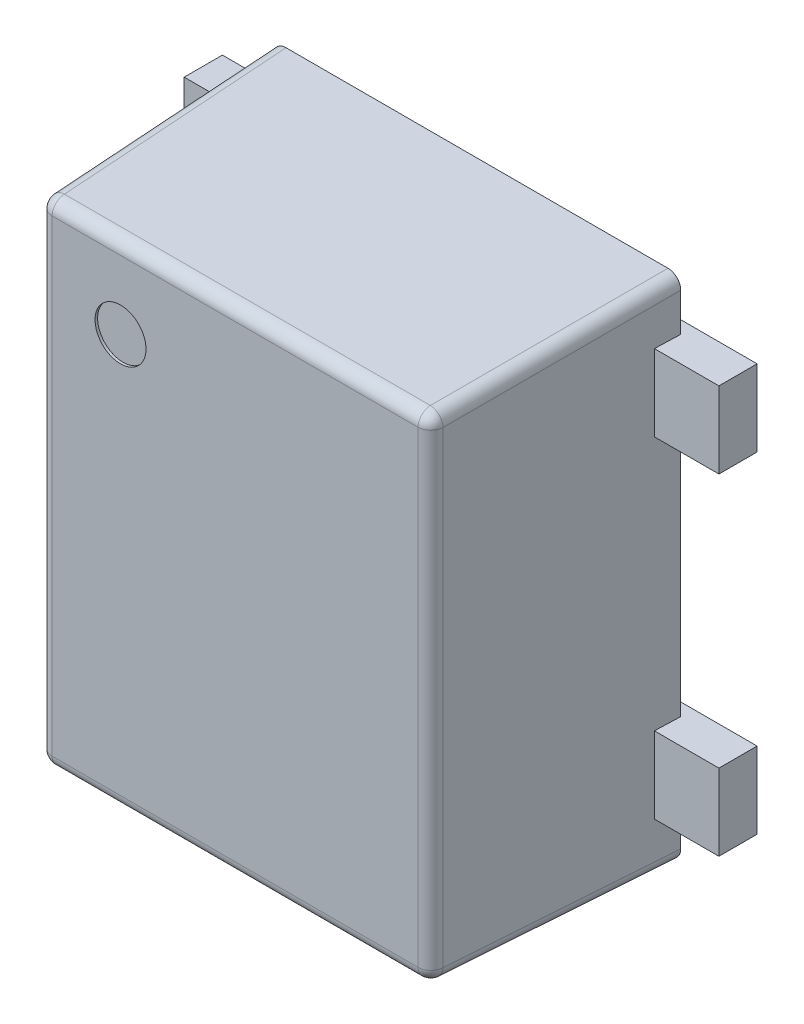
SolidWorks part; units mm, degrees
ref_plane "Front" through (0, 0, 0) normal (0, 0, 1) x (1, 0, 0)
ref_plane "Top" through (0, 0, 0) normal (0, 1, 0) x (1, 0, 0)
ref_plane "Right" through (0, 0, 0) normal (1, 0, 0) x (0, 0, -1)
ref_plane "Плоскость1" through (0, 0, 0.05) normal (0, 0, 1) x (1, 0, 0)
sketch "Эскиз1" plane through (0, 0, 0.05) normal (0, 0, 1) x (1, 0, 0)
  line L1 (-0.8, -1) -> (0.8, -1)
  line L2 (-0.8, -1) -> (-0.8, 1)
  line L3 (-0.8, 1) -> (0.8, 1)
  line L4 (0.8, -1) -> (0.8, 1)
  line L5 (-0.8, -1) -> (0.8, 1) construction
  line L6 (-0.8, 1) -> (0.8, -1) construction
  point P0 (0, 0)
  dimension "D1" = 2
  dimension "D2" = 1.6
extrude "Бобышка-Вытянуть1" add sketch "Эскиз1" along normal offset from surface 1 draft 2
sketch "Эскиз2" plane through (0, 0, 0) normal (0, 0, 1) x (1, 0, 0)
  line L0 (0.85, 0) -> (-0.85, 0) construction
  line L1 (0.65, 0.8) -> (1.05, 0.8)
  line L2 (0.65, 0.8) -> (0.65, 0.5)
  line L3 (0.65, 0.5) -> (1.05, 0.5)
  line L4 (1.05, 0.8) -> (1.05, 0.5)
  line L5 (0.65, 0.8) -> (1.05, 0.5) construction
  line L6 (0.65, 0.5) -> (1.05, 0.8) construction
  line L7 (0.65, -0.5) -> (1.05, -0.5)
  line L8 (0.65, -0.5) -> (0.65, -0.8)
  line L9 (0.65, -0.8) -> (1.05, -0.8)
  line L10 (1.05, -0.5) -> (1.05, -0.8)
  line L11 (0.65, -0.5) -> (1.05, -0.8) construction
  line L12 (0.65, -0.8) -> (1.05, -0.5) construction
  line L13 (-0.65, 0.5) -> (-1.05, 0.5)
  line L14 (-0.65, 0.5) -> (-0.65, 0.8)
  line L15 (-0.65, 0.8) -> (-1.05, 0.8)
  line L16 (-1.05, 0.5) -> (-1.05, 0.8)
  line L17 (-0.65, 0.5) -> (-1.05, 0.8) construction
  line L18 (-0.65, 0.8) -> (-1.05, 0.5) construction
  line L19 (-0.65, -0.8) -> (-1.05, -0.8)
  line L20 (-0.65, -0.8) -> (-0.65, -0.5)
  line L21 (-0.65, -0.5) -> (-1.05, -0.5)
  line L22 (-1.05, -0.8) -> (-1.05, -0.5)
  line L23 (-0.65, -0.8) -> (-1.05, -0.5) construction
  line L24 (-0.65, -0.5) -> (-1.05, -0.8) construction
  line L26 (0.85, -0.65) -> (0.85, 0.65) construction
  line L27 (-0.85, 0.65) -> (-0.85, -0.65) construction
  point P0 (0.85, 0.65)
  point P5 (0.85, -0.65)
  point P10 (-0.85, 0.65)
  point P15 (-0.85, -0.65)
  point P26 (0.1265, -1.3257)
  point P27 (-0.0379, 1.2748)
  point P28 (0, 0)
  point P30 (0.7858, -1.05)
  point P31 (-0.5359, -0.6159)
  point P32 (0.1136, -0.59)
  point P33 (-1.2028, -1.0624)
  point P34 (-0.9075, -0.6461)
  dimension "D1" = 2.1
  dimension "D2" = 0.3
  dimension "D3" = 0.4
  dimension "D4" = 0.65
extrude "Бобышка-Вытянуть2" add sketch "Эскиз2" along normal blind 0.15
fillet "Скругление1" radius 0.05 8 edges at (-0.7834, 0.9834, 0.525) (-0.7834, -0.9834, 0.525) (0, -0.9668, 1) (0.7834, -0.9834, 0.525) (0.7668, 0, 1) (0.7834, 0.9834, 0.525) (0, 0.9668, 1) (-0.7668, 0, 1)
sketch "Эскиз3" plane through (0, 0, 1) normal (0, 0, 1) x (1, 0, 0)
  line L1 (-0.45, 0.65) -> (-0.45, 0.9668) construction
  line L2 (-0.45, 0.65) -> (-0.7668, 0.65) construction
  line L3 (-0.7668, 0.9668) -> (-0.7668, -0.9668) construction
  line L4 (0.7668, 0.9668) -> (-0.7668, 0.9668) construction
  circle A0 centre (-0.45, 0.65) radius 0.1
  point P2 (0, 0)
  point P3 (-0.3372, -0.261)
  point P4 (-0.4072, -0.1624)
  point P5 (-0.2579, -0.4579)
  point P11 (-0.288, 0.9668)
  point P14 (-0.4706, 0.6706)
  dimension "D1" = 0.2
  dimension "D2" = 0.65
extrude "Вырез-Вытянуть1" cut sketch "Эскиз3" against normal blind 0.01 contours A0
